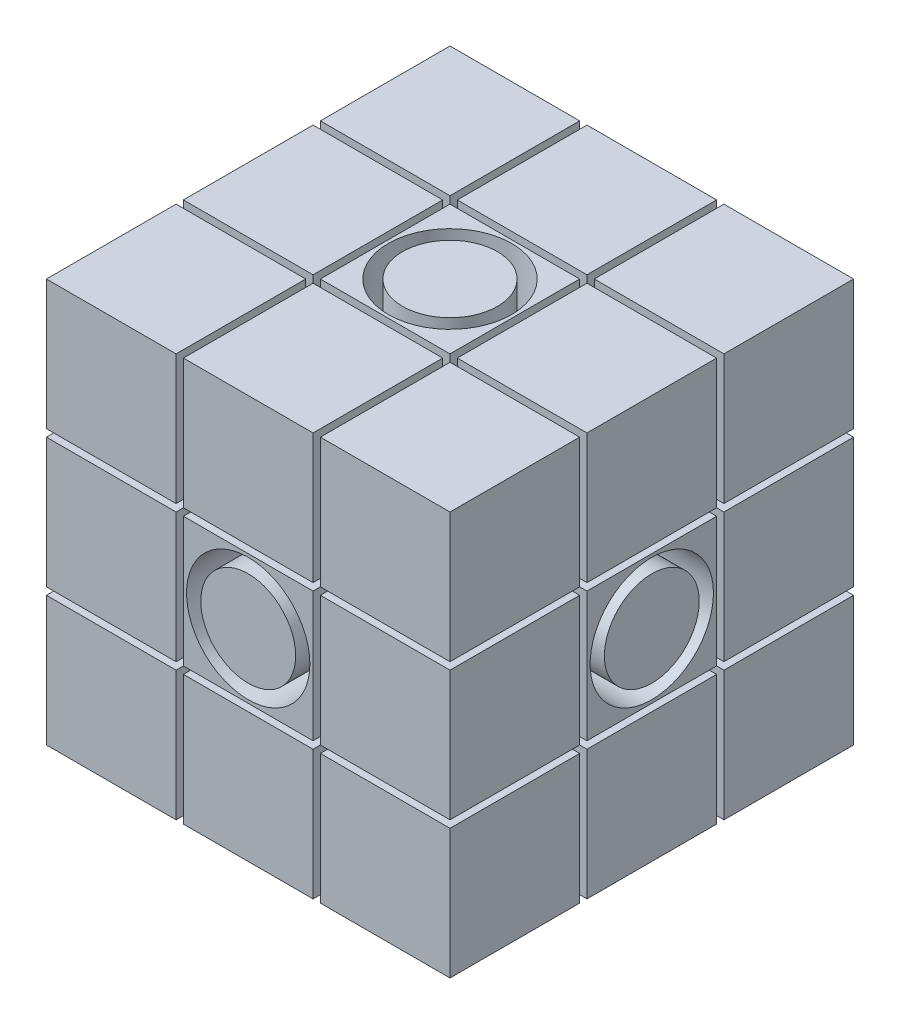
SolidWorks part; units mm, degrees
ref_plane "Front Plane" through (0, 0, 0) normal (0, 0, 1) x (1, 0, 0)
ref_plane "Top Plane" through (0, 0, 0) normal (0, 1, 0) x (1, 0, 0)
ref_plane "Right Plane" through (0, 0, 0) normal (1, 0, 0) x (0, 0, -1)
sketch "Sketch1" plane through (0, 0, 0) normal (0, 1, 0) x (1, 0, 0)
  line L1 (-27.65, 27.65) -> (27.65, 27.65)
  line L2 (-27.65, 27.65) -> (-27.65, -27.65)
  line L3 (-27.65, -27.65) -> (27.65, -27.65)
  line L4 (27.65, 27.65) -> (27.65, -27.65)
  point P0 (0, 0)
  dimension "D1" = 55.3
  dimension "D2" = 27.65
  dimension "D3" = 27.65
extrude "Boss-Extrude1" add sketch "Sketch1" along normal mid plane 55.3
sketch "Sketch2" plane through (0, 27.65, 0) normal (0, 1, 0) x (1, 0, 0)
  circle A0 centre (0, 0) radius 8.45
  circle A1 centre (0, 0) radius 6.5
  dimension "D1" = 16.9
  dimension "D2" = 13
extrude "Cut-Extrude2" cut sketch "Sketch2" against normal blind 9.5
sketch "Sketch3" plane through (0, -27.65, 0) normal (0, -1, 0) x (1, 0, 0)
  circle A0 centre (0, 0) radius 8.45
  circle A1 centre (0, 0) radius 6.5
  dimension "D1" = 16.9
  dimension "D2" = 13
extrude "Cut-Extrude3" cut sketch "Sketch3" against normal blind 9.5
sketch "Sketch4" plane through (27.65, 0, 0) normal (1, 0, 0) x (0, 0, -1)
  circle A0 centre (0, 0) radius 8.45
  circle A1 centre (0, 0) radius 6.5
  dimension "D1" = 16.9
  dimension "D2" = 13
extrude "Cut-Extrude4" cut sketch "Sketch4" against normal blind 9.5
sketch "Sketch5" plane through (-27.65, 0, 0) normal (-1, 0, 0) x (0, 0, 1)
  circle A0 centre (0, 0) radius 8.45
  circle A1 centre (0, 0) radius 6.5
  dimension "D1" = 16.9
  dimension "D2" = 13
extrude "Cut-Extrude5" cut sketch "Sketch5" against normal blind 9.5
sketch "Sketch6" plane through (0, 0, 27.65) normal (0, 0, 1) x (1, 0, 0)
  circle A0 centre (0, 0) radius 8.45
  circle A1 centre (0, 0) radius 6.5
  dimension "D1" = 16.9
  dimension "D2" = 13
extrude "Cut-Extrude6" cut sketch "Sketch6" against normal blind 9.5
sketch "Sketch7" plane through (0, 0, -27.65) normal (0, 0, -1) x (-1, 0, 0)
  circle A0 centre (0, 0) radius 8.45
  circle A1 centre (0, 0) radius 6.5
  dimension "D1" = 13
  dimension "D2" = 16.9
extrude "Cut-Extrude7" cut sketch "Sketch7" against normal blind 9.5
sketch "Sketch8" plane through (0, 0, 0) normal (0, 1, 0) x (1, 0, 0)
  line L0 (-9.8833, 27.65) -> (-9.8833, 9.8833)
  line L1 (27.65, 27.65) -> (-27.65, 27.65) construction
  line L2 (-9.8833, 9.8833) -> (-27.65, 9.8833)
  line L3 (-27.65, 27.65) -> (-27.65, -27.65) construction
  line L4 (-27.65, 9.8833) -> (-27.65, 8.8833)
  line L5 (-27.65, 8.8833) -> (-9.8833, 8.8833)
  line L6 (-9.8833, 8.8833) -> (-9.8833, -8.8833)
  line L7 (-9.8833, -8.8833) -> (-27.65, -8.8833)
  line L8 (-27.65, -8.8833) -> (-27.65, -9.8833)
  line L9 (-27.65, -9.8833) -> (-9.8833, -9.8833)
  line L10 (-9.8833, -9.8833) -> (-9.8833, -27.65)
  line L11 (-9.8833, -27.65) -> (-8.8833, -27.65)
  line L12 (-27.65, -27.65) -> (27.65, -27.65) construction
  line L13 (-8.8833, -27.65) -> (-8.8833, -9.8833)
  line L14 (-8.8833, -9.8833) -> (8.8833, -9.8833)
  line L15 (8.8833, -9.8833) -> (8.8833, -27.65)
  line L16 (8.8833, -27.65) -> (9.8833, -27.65)
  line L17 (9.8833, -27.65) -> (9.8833, -9.8833)
  line L18 (9.8833, -9.8833) -> (27.65, -9.8833)
  line L19 (27.65, -27.65) -> (27.65, 27.65) construction
  line L20 (27.65, -9.8833) -> (27.65, -8.8833)
  line L21 (27.65, -8.8833) -> (9.8833, -8.8833)
  line L22 (9.8833, -8.8833) -> (9.8833, 8.8833)
  line L23 (9.8833, 8.8833) -> (27.65, 8.8833)
  line L24 (27.65, 8.8833) -> (27.65, 9.8833)
  line L25 (27.65, 9.8833) -> (9.8833, 9.8833)
  line L26 (9.8833, 9.8833) -> (9.8833, 27.65)
  line L27 (9.8833, 27.65) -> (8.8833, 27.65)
  line L28 (8.8833, 27.65) -> (8.8833, 9.8833)
  line L29 (8.8833, 9.8833) -> (-8.8833, 9.8833)
  line L30 (-8.8833, 9.8833) -> (-8.8833, 27.65)
  line L31 (-8.8833, 27.65) -> (-9.8833, 27.65)
  line L32 (-8.8833, 8.8833) -> (8.8833, 8.8833)
  line L35 (-8.8833, -8.8833) -> (-8.8833, 8.8833)
  line L36 (8.8833, 8.8833) -> (8.8833, -8.8833)
  line L37 (8.8833, -8.8833) -> (-8.8833, -8.8833)
  dimension "D1" = 1
  dimension "D2" = 1
  dimension "D3" = 1
  dimension "D4" = 1
  dimension "D5" = 1
  dimension "D6" = 1
  dimension "D7" = 1
  dimension "D8" = 1
  dimension "D9" = 1
  dimension "D10" = 1
  dimension "D11" = 1
  dimension "D12" = 1
  dimension "D13" = 17.7667
  dimension "D14" = 17.7667
  dimension "D15" = 17.7667
  dimension "D16" = 17.7667
  dimension "D17" = 17.7667
  dimension "D18" = 17.7667
  dimension "D19" = 17.7667
  dimension "D20" = 17.7667
  dimension "D21" = 17.7667
  dimension "D22" = 17.7667
extrude "Cut-Extrude8" cut sketch "Sketch8" against normal mid plane 60
sketch "Sketch10" plane through (0, 0, 0) normal (0, 0, 1) x (1, 0, 0)
  line L0 (-27.65, 9.8833) -> (27.65, 9.8833)
  line L1 (-27.65, 27.65) -> (-27.65, -27.65) construction
  line L2 (27.65, 27.65) -> (27.65, -27.65) construction
  line L3 (27.65, 9.8833) -> (27.65, 8.8833)
  line L6 (-27.65, -8.8833) -> (27.65, -8.8833)
  line L7 (27.65, -8.8833) -> (27.65, -9.8833)
  line L8 (27.65, -9.8833) -> (-27.65, -9.8833)
  line L9 (-27.65, -9.8833) -> (-27.65, -8.8833)
  line L10 (27.65, 8.8833) -> (-27.65, 8.8833)
  line L12 (-27.65, 27.65) -> (-9.8833, 27.65) construction
  line L13 (-27.65, 9.8833) -> (-27.65, 8.8833)
  dimension "D1" = 1
  dimension "D2" = 1
  dimension "D3" = 17.7667
  dimension "D4" = 17.7667
extrude "Cut-Extrude9" cut sketch "Sketch10" against normal mid plane 120
